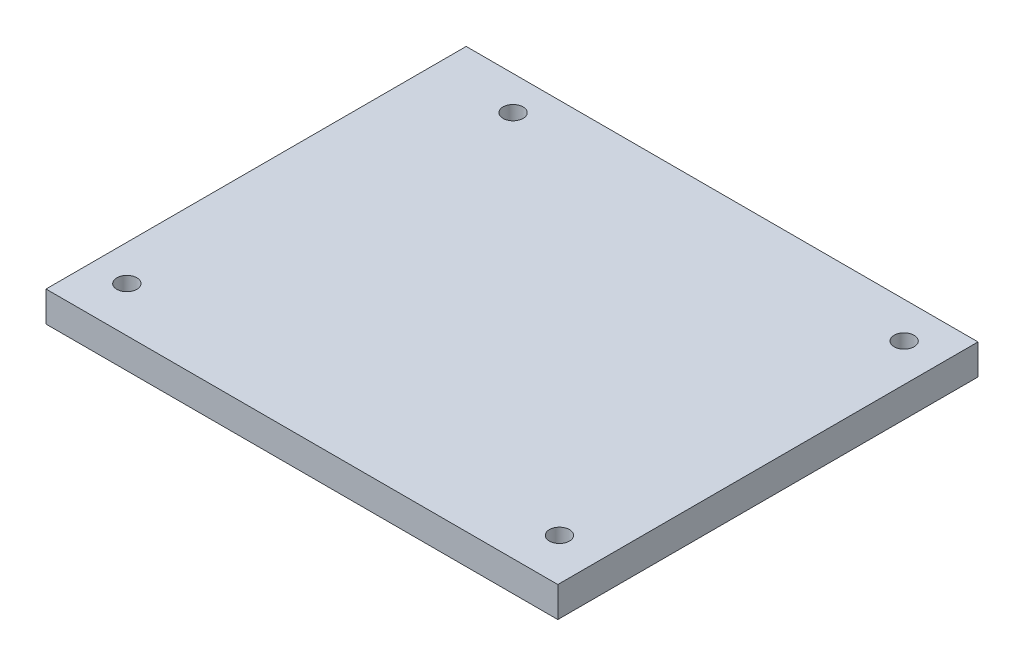
SolidWorks part; units mm, degrees
ref_plane "Front Plane" through (0, 0, 0) normal (0, 0, 1) x (1, 0, 0)
ref_plane "Top Plane" through (0, 0, 0) normal (0, 1, 0) x (1, 0, 0)
ref_plane "Right Plane" through (0, 0, 0) normal (1, 0, 0) x (0, 0, -1)
sketch "Sketch1" plane through (0, 0, 0) normal (0, 1, 0) x (1, 0, 0)
  line L1 (-45.55, 36.5) -> (45.55, 36.5) construction
  line L2 (-45.55, 36.5) -> (-45.55, -36.5) construction
  line L3 (-45.55, -36.5) -> (45.55, -36.5) construction
  line L4 (45.55, 36.5) -> (45.55, -36.5) construction
  line L5 (-45.55, 36.5) -> (45.55, -36.5) construction
  line L6 (-45.55, -36.5) -> (45.55, 36.5) construction
  line L7 (-50.55, -41.5) -> (50.55, -41.5)
  line L8 (-50.55, -41.5) -> (-50.55, 41.5)
  line L9 (-50.55, 41.5) -> (50.55, 41.5)
  line L10 (50.55, -41.5) -> (50.55, 41.5)
  line L11 (-50.55, -41.5) -> (50.55, 41.5) construction
  line L12 (-50.55, 41.5) -> (50.55, -41.5) construction
  circle A0 centre (-34.59, 34.8) radius 1.5 construction
  circle A1 centre (43.1, 34.36) radius 1.5 construction
  circle A2 centre (42.3, -32.93) radius 1.5 construction
  circle A3 centre (-43.5, -32.58) radius 1.5 construction
  circle A4 centre (43.1, 34.36) radius 1.98
  circle A5 centre (-34.59, 34.8) radius 1.98
  circle A6 centre (42.3, -32.93) radius 1.98
  circle A7 centre (-43.5, -32.58) radius 1.98
  point P0 (0, 0)
  point P17 (0, 0)
  dimension "D3" = 0.55
  dimension "D4" = 2.42
  dimension "D5" = 1.75
  dimension "D6" = 2.07
  dimension "D7" = 0.95
  dimension "D8" = 0.64
  dimension "D9" = 0.2
  dimension "D10" = 9.46
  dimension "D11" = 3
  dimension "D14" = 3.96
  dimension "D1" = 73
  dimension "D2" = 91.1
  dimension "D12" = 5
  dimension "D13" = 5
extrude "Boss-Extrude1" add sketch "Sketch1" along normal blind 6
